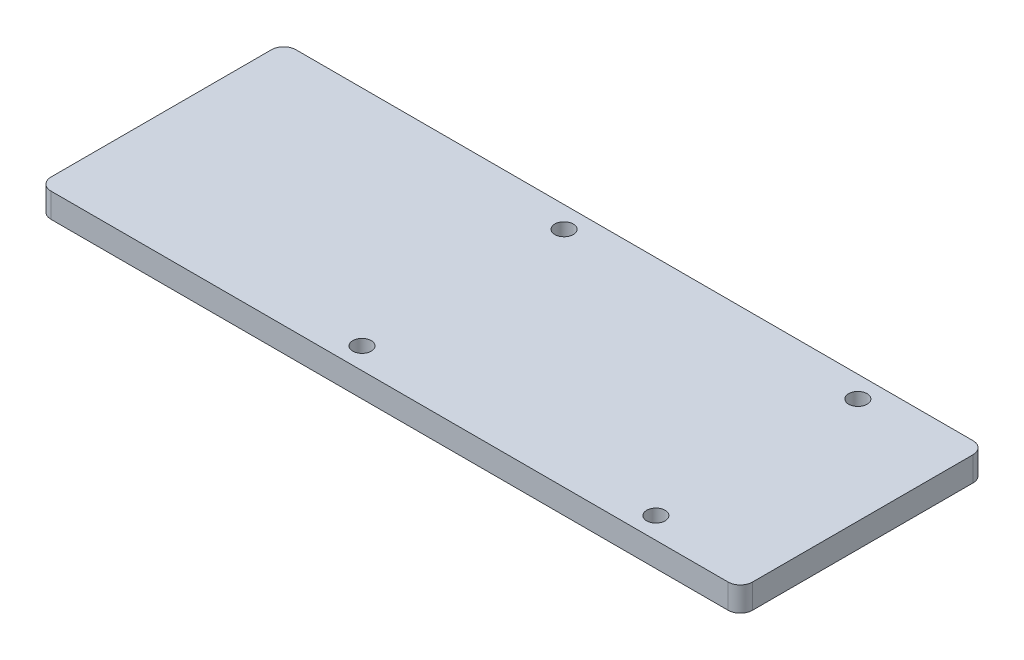
SolidWorks part; units mm, degrees
material "1060 Alloy"
ref_plane "Front Plane" through (0, 0, 0) normal (0, 0, 1) x (1, 0, 0)
ref_plane "Top Plane" through (0, 0, 0) normal (0, 1, 0) x (1, 0, 0)
ref_plane "Right Plane" through (0, 0, 0) normal (1, 0, 0) x (0, 0, -1)
sketch "Sketch1" plane through (0, 0, 0) normal (0, 1, 0) x (1, 0, 0)
  line L1 (-181.9, -63.5) -> (181.9, -63.5)
  line L2 (-181.9, -63.5) -> (-181.9, 63.5)
  line L3 (-181.9, 63.5) -> (181.9, 63.5)
  line L4 (181.9, -63.5) -> (181.9, 63.5)
  line L5 (-181.9, -63.5) -> (181.9, 63.5) construction
  line L6 (-181.9, 63.5) -> (181.9, -63.5) construction
  point P0 (0, 0)
  dimension "D1" = 127
  dimension "D2" = 363.8
extrude "Boss-Extrude1" add sketch "Sketch1" along normal blind 12.7
fillet "Fillet1" radius 6.35 4 edges at (-181.9, 6.35, -63.5) (181.9, 6.35, -63.5) (181.9, 6.35, 63.5) (-181.9, 6.35, 63.5)
sketch "Sketch2" plane through (0, 12.7, 0) normal (0, 1, 0) x (1, 0, 0)
  line L0 (-181.9, 0) -> (181.9, 0) construction
  line L3 (-181.9, 57.15) -> (-181.9, -57.15) construction
  line L4 (181.9, -57.15) -> (181.9, 57.15) construction
  line L5 (0, 63.5) -> (0, -63.5) construction
  line L6 (175.55, 63.5) -> (-175.55, 63.5) construction
  line L7 (-175.55, -63.5) -> (175.55, -63.5) construction
  circle A0 centre (-25.4, 52.3748) radius 4.7752
  circle A1 centre (-25.4, -52.3748) radius 4.7752
  circle A2 centre (127, -52.3748) radius 4.7752
  circle A3 centre (127, 52.3748) radius 4.7752
  point P14 (-25.4, 57.15)
  point P15 (0, 0)
  point P22 (0, 0)
  dimension "D1" = 9.5504
  dimension "D4" = 9.5504
  dimension "D2" = 6.35
  dimension "D3" = 25.4
  dimension "D5" = 127
  dimension "D6" = 127
extrude "Cut-Extrude1" cut sketch "Sketch2" against normal through all
